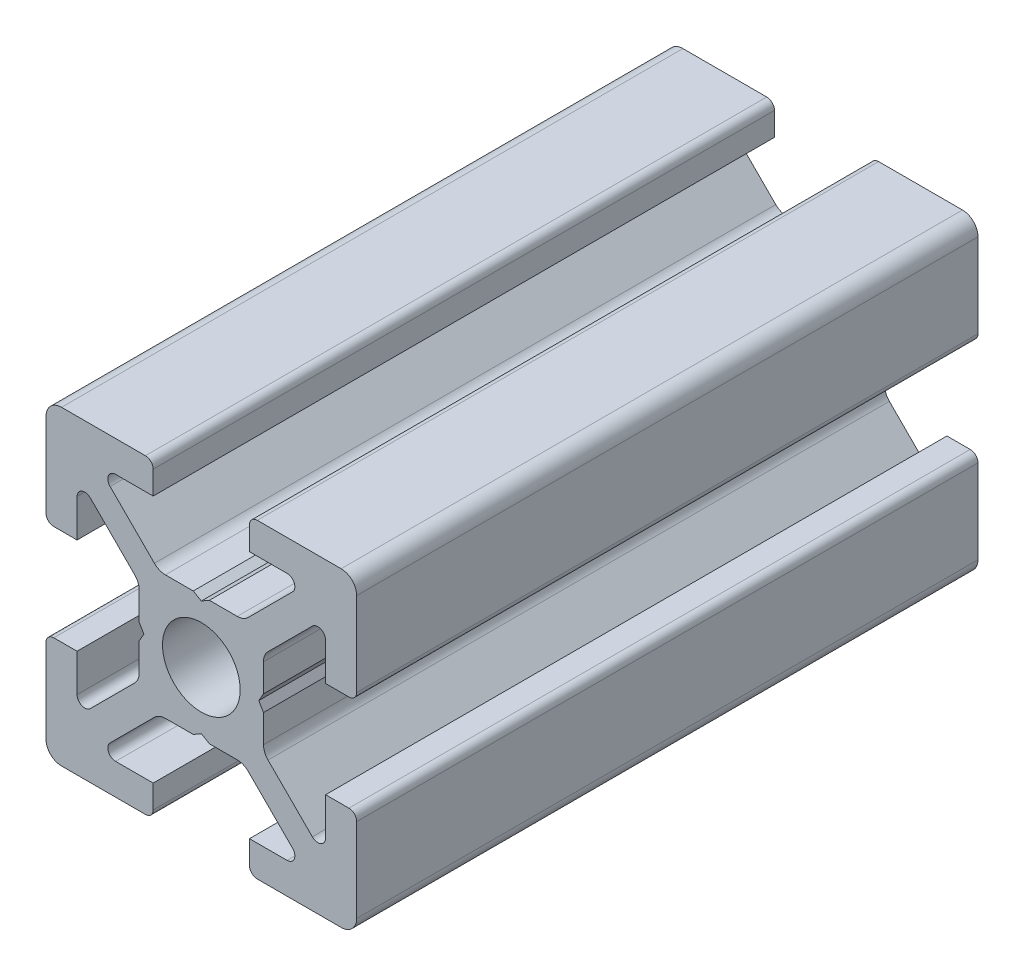
SolidWorks part; units mm, degrees
ref_plane "前视基准面" through (0, 0, 0) normal (0, 0, 1) x (1, 0, 0)
ref_plane "上视基准面" through (0, 0, 0) normal (0, 1, 0) x (1, 0, 0)
ref_plane "右视基准面" through (0, 0, 0) normal (1, 0, 0) x (0, 0, -1)
sketch "草图1" plane through (0, 0, 0) normal (0, 0, 1) x (1, 0, 0)
  line L0 (16.4868, 27.1233) -> (19.3403, 24.2698)
  line L1 (20.1939, 24.6233) -> (20.1939, 27.0434)
  line L2 (20.1939, 27.0434) -> (21.6939, 27.0434)
  line L3 (15.8939, 30.1434) -> (16.1939, 29.6238)
  line L4 (12.1939, 33.8434) -> (12.7135, 34.1434)
  line L5 (22.1939, 26.5434) -> (22.1939, 21.1434)
  line L6 (21.1939, 20.1434) -> (15.7939, 20.1434)
  line L7 (12.1939, 33.8434) -> (11.6743, 34.1434)
  line L8 (12.7135, 34.1434) -> (14.5069, 34.1434)
  line L9 (15.2939, 20.6434) -> (15.2939, 22.1434)
  line L10 (15.2939, 22.1434) -> (17.714, 22.1434)
  line L11 (18.0675, 22.997) -> (15.214, 25.8506)
  line L12 (14.5069, 26.1434) -> (12.7135, 26.1434)
  line L13 (9.1738, 25.8506) -> (6.3202, 22.997)
  line L14 (6.6738, 22.1434) -> (9.0939, 22.1434)
  line L15 (9.0939, 22.1434) -> (9.0939, 20.6434)
  line L16 (15.8939, 30.1434) -> (16.1939, 30.6631)
  line L17 (12.1939, 26.4434) -> (11.6743, 26.1434)
  line L18 (8.5939, 20.1434) -> (3.1939, 20.1434)
  line L19 (2.1939, 21.1434) -> (2.1939, 26.5434)
  line L20 (12.1939, 26.4434) -> (12.7135, 26.1434)
  line L21 (8.4939, 30.1434) -> (8.1939, 30.6631)
  line L22 (2.6939, 27.0434) -> (4.1939, 27.0434)
  line L23 (4.1939, 27.0434) -> (4.1939, 24.6233)
  line L24 (5.0474, 24.2698) -> (7.901, 27.1233)
  line L25 (8.1939, 27.8305) -> (8.1939, 29.6238)
  line L26 (7.901, 33.1635) -> (5.0474, 36.0171)
  line L27 (4.1939, 35.6635) -> (4.1939, 33.2434)
  line L28 (4.1939, 33.2434) -> (2.6939, 33.2434)
  line L29 (8.4939, 30.1434) -> (8.1939, 29.6238)
  line L30 (16.1939, 29.6238) -> (16.1939, 27.8305)
  line L31 (2.1939, 33.7434) -> (2.1939, 39.1434)
  line L32 (3.1939, 40.1434) -> (8.5939, 40.1434)
  line L33 (11.6743, 26.1434) -> (9.8809, 26.1434)
  line L34 (8.1939, 30.6631) -> (8.1939, 32.4564)
  line L35 (9.0939, 39.6434) -> (9.0939, 38.1434)
  line L36 (9.0939, 38.1434) -> (6.6738, 38.1434)
  line L37 (6.3202, 37.2899) -> (9.1738, 34.4363)
  line L38 (9.8809, 34.1434) -> (11.6743, 34.1434)
  line L39 (15.214, 34.4363) -> (18.0675, 37.2899)
  line L40 (17.714, 38.1434) -> (15.2939, 38.1434)
  line L41 (15.2939, 38.1434) -> (15.2939, 39.6434)
  line L44 (15.7939, 40.1434) -> (21.1939, 40.1434)
  line L45 (22.1939, 39.1434) -> (22.1939, 33.7434)
  line L48 (21.6939, 33.2434) -> (20.1939, 33.2434)
  line L49 (20.1939, 33.2434) -> (20.1939, 35.6635)
  line L50 (19.3403, 36.0171) -> (16.4868, 33.1635)
  line L51 (16.1939, 32.4564) -> (16.1939, 30.6631)
  circle A0 centre (12.1939, 30.1434) radius 2.5
  arc A1 (16.1939, 27.8305) -> (16.4868, 27.1233) centre (17.1939, 27.8305) ccw
  arc A2 (19.3403, 24.2698) -> (20.1939, 24.6233) centre (19.6939, 24.6233) ccw
  arc A3 (21.1939, 20.1434) -> (22.1939, 21.1434) centre (21.1939, 21.1434) ccw
  arc A4 (17.714, 22.1434) -> (18.0675, 22.997) centre (17.714, 22.6434) ccw
  arc A5 (15.214, 25.8506) -> (14.5069, 26.1434) centre (14.5069, 25.1434) ccw
  arc A6 (9.8809, 26.1434) -> (9.1738, 25.8506) centre (9.8809, 25.1434) ccw
  arc A7 (6.3202, 22.997) -> (6.6738, 22.1434) centre (6.6738, 22.6434) ccw
  arc A8 (2.1939, 21.1434) -> (3.1939, 20.1434) centre (3.1939, 21.1434) ccw
  arc A9 (4.1939, 24.6233) -> (5.0474, 24.2698) centre (4.6939, 24.6233) ccw
  arc A10 (7.901, 27.1233) -> (8.1939, 27.8305) centre (7.1939, 27.8305) ccw
  arc A11 (8.1939, 32.4564) -> (7.901, 33.1635) centre (7.1939, 32.4564) ccw
  arc A12 (5.0474, 36.0171) -> (4.1939, 35.6635) centre (4.6939, 35.6635) ccw
  arc A13 (3.1939, 40.1434) -> (2.1939, 39.1434) centre (3.1939, 39.1434) ccw
  arc A14 (6.6738, 38.1434) -> (6.3202, 37.2899) centre (6.6738, 37.6434) ccw
  arc A15 (9.1738, 34.4363) -> (9.8809, 34.1434) centre (9.8809, 35.1434) ccw
  arc A16 (14.5069, 34.1434) -> (15.214, 34.4363) centre (14.5069, 35.1434) ccw
  arc A17 (18.0675, 37.2899) -> (17.714, 38.1434) centre (17.714, 37.6434) ccw
  arc A18 (22.1939, 39.1434) -> (21.1939, 40.1434) centre (21.1939, 39.1434) ccw
  arc A19 (20.1939, 35.6635) -> (19.3403, 36.0171) centre (19.6939, 35.6635) ccw
  arc A20 (16.4868, 33.1635) -> (16.1939, 32.4564) centre (17.1939, 32.4564) ccw
  arc A21 (15.7939, 20.1434) -> (15.2939, 20.6434) centre (15.7939, 20.6434) cw
  arc A22 (9.0939, 20.6434) -> (8.5939, 20.1434) centre (8.5939, 20.6434) cw
  arc A23 (2.1939, 26.5434) -> (2.6939, 27.0434) centre (2.6939, 26.5434) cw
  arc A24 (2.6939, 33.2434) -> (2.1939, 33.7434) centre (2.6939, 33.7434) cw
  arc A25 (22.1939, 26.5434) -> (21.6939, 27.0434) centre (21.6939, 26.5434) ccw
  arc A26 (21.6939, 33.2434) -> (22.1939, 33.7434) centre (21.6939, 33.7434) ccw
  arc A27 (15.7939, 40.1434) -> (15.2939, 39.6434) centre (15.7939, 39.6434) ccw
  arc A28 (9.0939, 39.6434) -> (8.5939, 40.1434) centre (8.5939, 39.6434) ccw
  dimension "D1" = 0.5
  dimension "D2" = 4
extrude "凸台-拉伸1" add sketch "草图1" along normal blind 40
